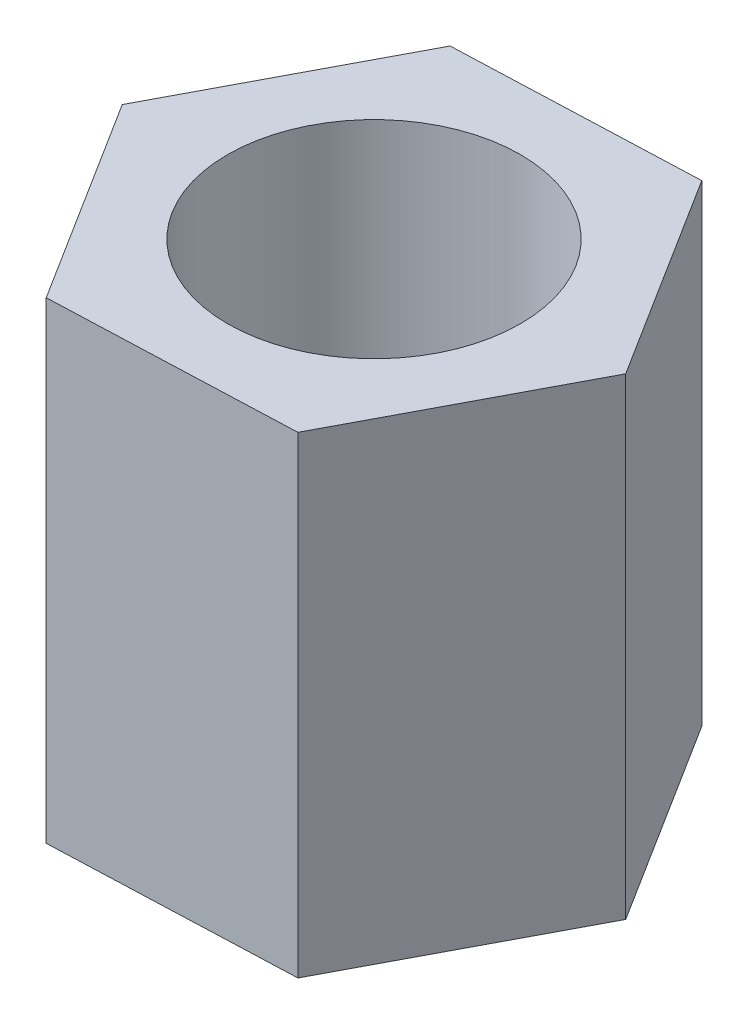
SolidWorks part; units mm, degrees
ref_plane "Front Plane" through (0, 0, 0) normal (0, 0, 1) x (1, 0, 0)
ref_plane "Top Plane" through (0, 0, 0) normal (0, 1, 0) x (1, 0, 0)
ref_plane "Right Plane" through (0, 0, 0) normal (1, 0, 0) x (0, 0, -1)
sketch "Sketch2" plane through (0, 0, 0) normal (0, 1, 0) x (1, 0, 0)
  line L1 (2.5653, 0.0981) -> (1.1976, 2.2707)
  line L2 (1.1976, 2.2707) -> (-1.3676, 2.1725)
  line L3 (-1.3676, 2.1725) -> (-2.5653, -0.0981)
  line L4 (-2.5653, -0.0981) -> (-1.1976, -2.2707)
  line L5 (-1.1976, -2.2707) -> (1.3676, -2.1725)
  line L6 (1.3676, -2.1725) -> (2.5653, 0.0981)
  circle A0 centre (0, 0) radius 1.55
  circle A1 centre (0, 0) radius 2.2232 construction
extrude "Boss-Extrude1" add sketch "Sketch2" along normal blind 5
